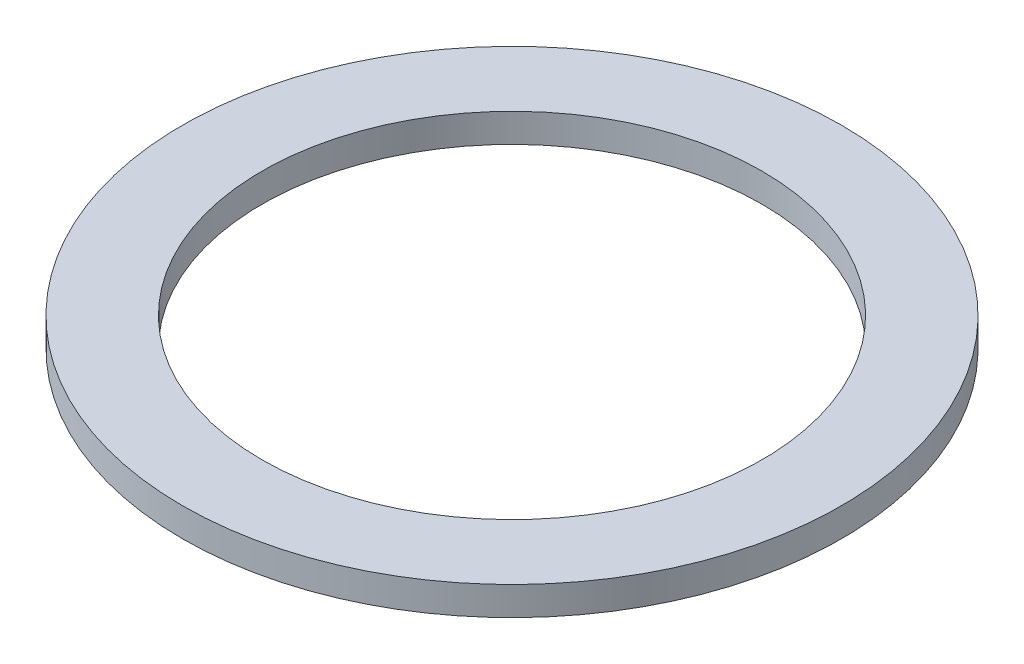
SolidWorks part; units mm, degrees
material "Copper"
ref_plane "Front Plane" through (0, 0, 0) normal (0, 0, 1) x (1, 0, 0)
ref_plane "Top Plane" through (0, 0, 0) normal (0, 1, 0) x (1, 0, 0)
ref_plane "Right Plane" through (0, 0, 0) normal (1, 0, 0) x (0, 0, -1)
sketch "Sketch1" plane through (0, 0, 0) normal (0, 1, 0) x (1, 0, 0)
  circle A0 centre (0, 0) radius 24.12
  circle A1 centre (0, 0) radius 18.3
  dimension "D1" = 48.24
  dimension "D2" = 36.6
extrude "Boss-Extrude1" add sketch "Sketch1" along normal blind 2.1
